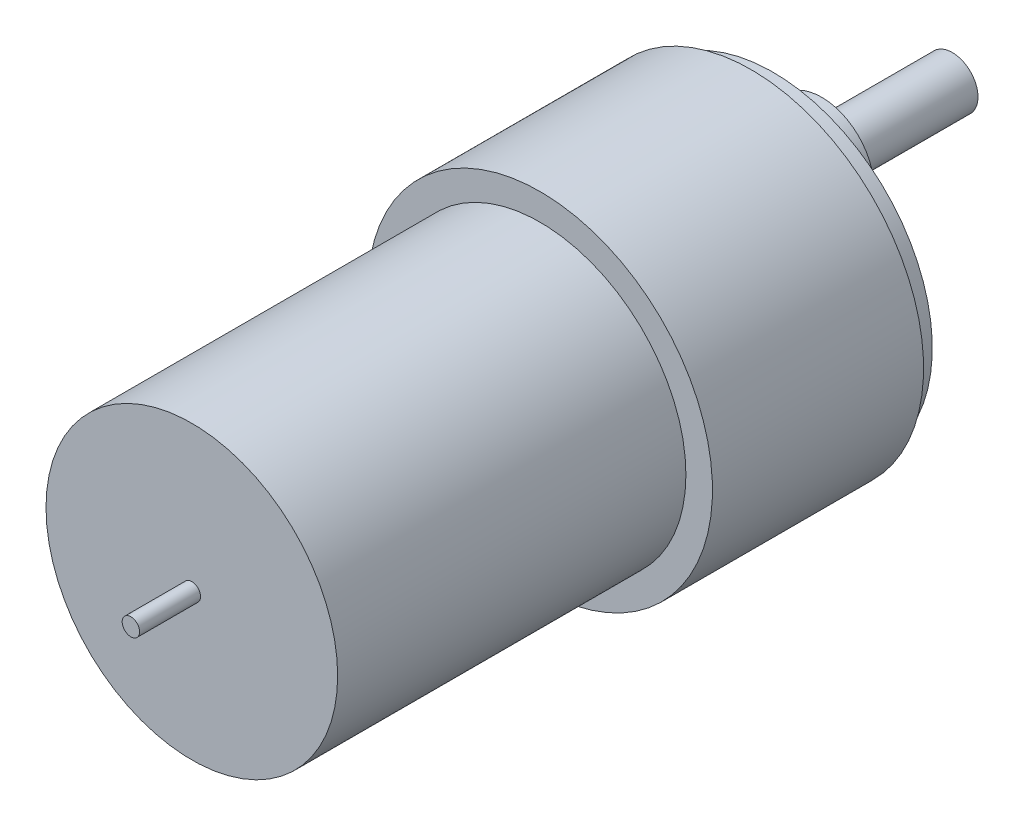
SolidWorks part; units mm, degrees
ref_plane "Front Plane" through (0, 0, 0) normal (0, 0, 1) x (1, 0, 0)
ref_plane "Top Plane" through (0, 0, 0) normal (0, 1, 0) x (1, 0, 0)
ref_plane "Right Plane" through (0, 0, 0) normal (1, 0, 0) x (0, 0, -1)
sketch "Sketch1" plane through (0, 0, 0) normal (0, 0, 1) x (1, 0, 0)
  circle A0 centre (0, 0) radius 19.8
  dimension "D1" = 39.6
extrude "gearbox" add sketch "Sketch1" along normal blind 24.25
sketch "Sketch2" plane through (0, 0, 24.25) normal (0, 0, 1) x (1, 0, 0)
  circle A0 centre (0, 0) radius 16.75
  dimension "D1" = 33.5
extrude "motor" add sketch "Sketch2" along normal blind 40
sketch "Sketch3" plane through (0, 0, 0) normal (0, 0, -1) x (-1, 0, 0)
  circle A0 centre (0, 0) radius 18.3
  dimension "D1" = 36.6
extrude "gearbox lip" add sketch "Sketch3" along normal blind 2.5
sketch "Sketch4" plane through (0, 0, -2.5) normal (0, 0, -1) x (-1, 0, 0)
  line L0 (-26.2106, 13) -> (33.7172, 13) construction
  line L1 (-39.0327, -18.3) -> (25.6626, -18.3) construction
  circle A0 centre (0, 7) radius 6
  circle A1 centre (0, 0) radius 18.3 construction
  dimension "D1" = 12
  dimension "D2" = 7
extrude "shaft hub" add sketch "Sketch4" along normal blind 5.6
sketch "Sketch5" plane through (0, 0, -8.1) normal (0, 0, -1) x (-1, 0, 0)
  line L0 (-1.7154, 4.6) -> (1.7154, 4.6)
  line L1 (-11.7011, 9.95) -> (9.5104, 9.95) construction
  arc A1 (-1.7154, 4.6) -> (1.7154, 4.6) centre (0, 7) cw
  circle A2 centre (0, 7) radius 6 construction
  dimension "D1" = 2.95
  dimension "D2" = 5.35
extrude "shaft" add sketch "Sketch5" along normal blind 15
sketch "Sketch6" plane through (0, 0, -2.5) normal (0, 0, -1) x (-1, 0, 0)
  circle A0 centre (-15.5, 0) radius 1.5
  dimension "D1" = 3
  dimension "D2" = 15.5
extrude "mnt screw hole" cut sketch "Sketch6" against normal blind 4
pattern_circular "CirPattern1" count 6 over 360 about axis through (0, 0, 0) along (0, 0, 1) of "mnt screw hole"
sketch "Sketch7" plane through (0, 0, 64.25) normal (0, 0, 1) x (1, 0, 0)
  circle A0 centre (0, 0) radius 1
  dimension "D1" = 2
extrude "sensorshaft" add sketch "Sketch7" along normal blind 7
